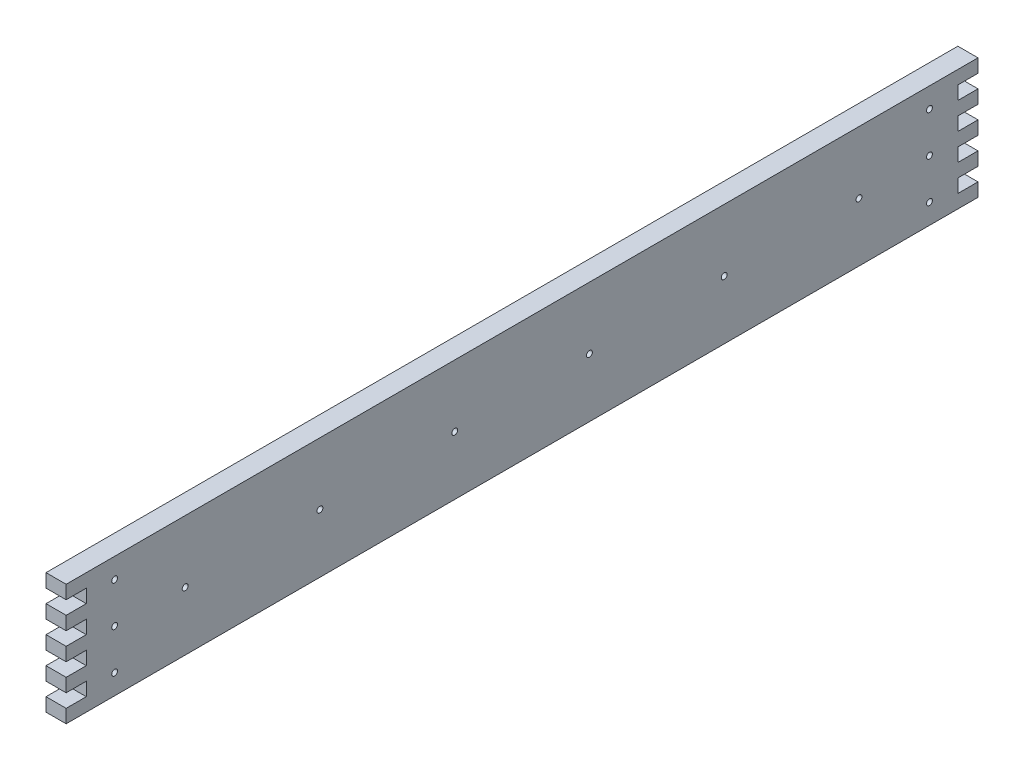
SolidWorks part; units mm, degrees
material "Pine"
ref_plane "Front Plane" through (0, 0, 0) normal (0, 0, 1) x (1, 0, 0)
ref_plane "Top Plane" through (0, 0, 0) normal (0, 1, 0) x (1, 0, 0)
ref_plane "Right Plane" through (0, 0, 0) normal (1, 0, 0) x (0, 0, -1)
sketch "Sketch1" plane through (0, 0, 0) normal (1, 0, 0) x (0, 0, -1)
  line L0 (19.05, 114.3) -> (19.05, 101.6) construction
  line L1 (0, 0) -> (862.33, 0)
  line L2 (0, 0) -> (0, 12.7)
  line L3 (0, 114.3) -> (862.33, 114.3)
  line L4 (862.33, 0) -> (862.33, 12.7)
  line L5 (0, 0) -> (862.33, 114.3) construction
  line L6 (0, 114.3) -> (862.33, 0) construction
  line L7 (0, 101.6) -> (19.05, 101.6)
  line L9 (0, 88.9) -> (19.05, 88.9)
  line L10 (0, 76.2) -> (19.05, 76.2)
  line L12 (0, 63.5) -> (19.05, 63.5)
  line L13 (19.05, 76.2) -> (19.05, 63.5)
  line L14 (0, 76.2) -> (19.05, 63.5) construction
  line L15 (0, 63.5) -> (19.05, 76.2) construction
  line L16 (0, 50.8) -> (19.05, 50.8)
  line L18 (0, 38.1) -> (19.05, 38.1)
  line L19 (19.05, 50.8) -> (19.05, 38.1)
  line L20 (0, 50.8) -> (19.05, 38.1) construction
  line L21 (0, 38.1) -> (19.05, 50.8) construction
  line L22 (0, 25.4) -> (19.05, 25.4)
  line L24 (0, 12.7) -> (19.05, 12.7)
  line L25 (19.05, 25.4) -> (19.05, 12.7)
  line L26 (0, 25.4) -> (19.05, 12.7) construction
  line L27 (0, 12.7) -> (19.05, 25.4) construction
  line L28 (19.05, 101.6) -> (19.05, 88.9)
  line L29 (0, 101.6) -> (19.05, 88.9) construction
  line L30 (0, 88.9) -> (19.05, 101.6) construction
  line L31 (19.05, 88.9) -> (19.05, 76.2) construction
  line L32 (19.05, 63.5) -> (19.05, 50.8) construction
  line L33 (19.05, 38.1) -> (19.05, 25.4) construction
  line L34 (19.05, 12.7) -> (19.05, 0) construction
  line L35 (0, 101.6) -> (0, 114.3)
  line L36 (0, 76.2) -> (0, 88.9)
  line L37 (0, 50.8) -> (0, 63.5)
  line L38 (0, 25.4) -> (0, 38.1)
  line L39 (431.165, 114.3) -> (431.165, 0) construction
  line L40 (862.33, 12.7) -> (843.28, 12.7)
  line L41 (843.28, 25.4) -> (843.28, 12.7)
  line L42 (862.33, 25.4) -> (843.28, 25.4)
  line L43 (862.33, 38.1) -> (843.28, 38.1)
  line L44 (843.28, 50.8) -> (843.28, 38.1)
  line L45 (862.33, 50.8) -> (843.28, 50.8)
  line L46 (862.33, 63.5) -> (843.28, 63.5)
  line L47 (843.28, 76.2) -> (843.28, 63.5)
  line L48 (862.33, 76.2) -> (843.28, 76.2)
  line L49 (862.33, 88.9) -> (843.28, 88.9)
  line L50 (843.28, 101.6) -> (843.28, 88.9)
  line L51 (862.33, 101.6) -> (843.28, 101.6)
  line L52 (862.33, 101.6) -> (862.33, 114.3)
  line L53 (862.33, 76.2) -> (862.33, 88.9)
  line L54 (862.33, 50.8) -> (862.33, 63.5)
  line L55 (862.33, 25.4) -> (862.33, 38.1)
  point P4 (431.165, 57.15)
  point P14 (9.525, 69.85)
  point P19 (9.525, 44.45)
  point P24 (9.525, 19.05)
  point P25 (9.525, 95.25)
  dimension "D1" = 12.7
  dimension "D2" = 19.05
  dimension "D3" = 114.3
  dimension "D4" = 824.23
extrude "Boss-Extrude1" add sketch "Sketch1" along normal blind 19.05
hole_wizard "7/32 (0.21875) Diameter Hole2" positions "Sketch2" profile "Sketch3" hole size "7/32" standard "ANSI Inch" end condition up to next
sketch "Sketch2" plane through (19.05, 0, 0) normal (1, 0, 0) x (0, 0, -1)
  line L0 (45.8851, 55.499) -> (112.5601, 55.499) construction
  line L1 (112.5601, 55.499) -> (240.0021, 55.499) construction
  line L2 (240.0021, 55.499) -> (367.444, 55.499) construction
  line L3 (367.444, 55.499) -> (494.886, 55.499) construction
  line L4 (494.886, 55.499) -> (622.3279, 55.499) construction
  line L5 (622.3279, 55.499) -> (749.7699, 55.499) construction
  line L6 (749.7699, 55.499) -> (816.4449, 55.499) construction
  line L8 (816.4449, 95.25) -> (816.4449, 19.05) construction
  line L10 (45.8851, 95.25) -> (45.8851, 19.05) construction
  line L12 (45.8851, 19.05) -> (45.8851, 0) construction
  line L13 (0, 0) -> (862.33, 0) construction
  line L15 (45.8851, 95.25) -> (45.8851, 114.3) construction
  line L16 (862.33, 114.3) -> (0, 114.3) construction
  line L19 (816.4449, 95.25) -> (816.4449, 114.3) construction
  line L21 (816.4449, 19.05) -> (816.4449, 0) construction
  line L22 (431.165, 114.3) -> (431.165, 0) construction
  point P2 (112.5601, 55.499)
  point P4 (240.0021, 55.499)
  point P5 (367.444, 55.499)
  point P6 (494.886, 55.499)
  point P8 (622.3279, 55.499)
  point P10 (749.7699, 55.499)
  point P13 (816.4449, 95.25)
  point P14 (816.4449, 19.05)
  point P18 (45.8851, 95.25)
  point P19 (45.8851, 19.05)
  point P69 (45.8851, 57.15)
  point P72 (816.4449, 57.15)
  dimension "D1" = 19.05
  dimension "D2" = 637.2098
  dimension "D3" = 55.499
  dimension "D4" = 770.5598
  dimension "D5" = 38.1
  dimension "D6" = 38.1
sketch "Sketch3" plane through (19.05, 57.15, -816.4449) normal (0, 1, 0) x (0, 0, -1)
  line L0 (0, 0) -> (0, 19.05)
  line L1 (0, 19.05) -> (2.7781, 19.05)
  line L2 (2.7781, 19.05) -> (2.7781, 0)
  line L5 (2.7781, 0) -> (0, 0)
  line L11 (0, -6.35) -> (0, 107.95) construction
  dimension "Thru Hole Dia." = 5.5562
  dimension "Thru Hole Depth" = 19.05
